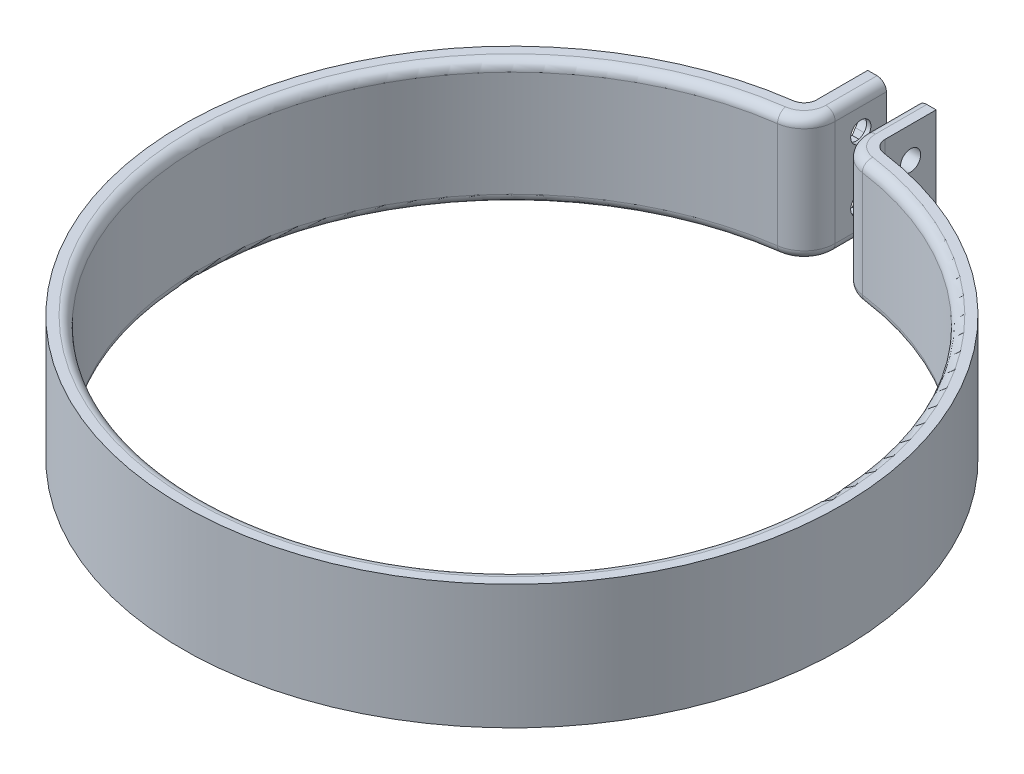
SolidWorks part; units mm, degrees
ref_plane "Front Plane" through (0, 0, 0) normal (0, 0, 1) x (1, 0, 0)
ref_plane "Top Plane" through (0, 0, 0) normal (0, 1, 0) x (1, 0, 0)
ref_plane "Right Plane" through (0, 0, 0) normal (1, 0, 0) x (0, 0, -1)
sketch "Sketch1" plane through (0, 0, 0) normal (0, 1, 0) x (1, 0, 0)
  line L0 (-74.3255, 0) -> (75.7723, 0) construction
  line L1 (0, 75.6818) -> (0, -79.2987) construction
  line L7 (2.5, 62.7139) -> (5.5, 62.7139)
  line L8 (2.5, 49.9375) -> (2.5, 62.7139)
  line L10 (-2.5, 49.9375) -> (-2.5, 62.7139)
  line L14 (-5.5, 52.7139) -> (-5.5, 62.7139)
  line L16 (5.5, 52.7139) -> (5.5, 62.7139)
  line L17 (2.5, 54.9432) -> (2.5, 67.7195) construction
  line L18 (-2.5, 62.7139) -> (-5.5, 62.7139)
  arc A1 (-2.5, 49.9375) -> (2.5, 49.9375) centre (0, 0) ccw
  arc A2 (-5.5, 52.7139) -> (5.5, 52.7139) centre (0, 0) ccw
  point P8 (-53, 0)
  point P9 (-50, 0)
  dimension "D1" = 3
  dimension "D2" = 100
  dimension "D5" = 10
  dimension "D6" = 5
  dimension "D7" = 3
  dimension "D8" = 5.5
extrude "Boss-Extrude1" add sketch "Sketch1" along normal blind 20
fillet "Fillet1" radius 5 2 edges at (-2.5, 10, -49.9375) (2.5, 10, -49.9375)
fillet "Fillet2" radius 2 2 edges at (-5.5, 10, -52.7139) (5.5, 10, -52.7139)
fillet "Fillet3" radius 1.5 10 edges at (-2.5, 0, -58.6) (-3.7311, 0, -51.2006) (-2.5, 20, -58.6) (-3.7311, 20, -51.2006) (0, 0, 50) (0, 20, 50) (2.5, 0, -58.6) (3.7311, 0, -51.2006) (2.5, 20, -58.6) (3.7311, 20, -51.2006)
sketch "Sketch4" plane through (-5.5, 0, 0) normal (-1, 0, 0) x (0, 0, 1)
  line L0 (-62.7139, 20) -> (-54.4862, 20) construction
  line L1 (-62.7139, 0) -> (-54.4862, 0) construction
  circle A0 centre (-58.6, 15) radius 2.9
  circle A1 centre (-58.6, 5) radius 2.9
  point P0 (-58.6, 20)
  point P1 (-58.6, 0)
  dimension "D1" = 5.8
  dimension "D2" = 5
  dimension "D3" = 5
extrude "Cut-Extrude3" cut sketch "Sketch4" against normal blind 2
sketch "Sketch5" plane through (-5.5, 0, 0) normal (-1, 0, 0) x (0, 0, 1)
  circle A0 centre (-58.6, 15) radius 1.625
  circle A1 centre (-58.6, 5) radius 1.625
  dimension "D1" = 3.25
extrude "Cut-Extrude4" cut sketch "Sketch5" against normal through all
sketch "Sketch6" plane through (-5.5, 0, 0) normal (-1, 0, 0) x (0, 0, 1)
  line L0 (-58.6, 17.825) -> (-58.6, 12.175) construction
  line L1 (-55.338, 15) -> (-56.969, 17.825)
  line L2 (-56.969, 17.825) -> (-60.2311, 17.825)
  line L3 (-60.2311, 17.825) -> (-61.8621, 15)
  line L4 (-61.8621, 15) -> (-60.2311, 12.175)
  line L5 (-60.2311, 12.175) -> (-56.969, 12.175)
  line L6 (-56.969, 12.175) -> (-55.338, 15)
  line L7 (-58.6, 7.825) -> (-58.6, 2.175) construction
  line L8 (-55.338, 5) -> (-56.969, 7.825)
  line L9 (-56.969, 7.825) -> (-60.2311, 7.825)
  line L10 (-60.2311, 7.825) -> (-61.8621, 5)
  line L11 (-61.8621, 5) -> (-60.2311, 2.175)
  line L12 (-60.2311, 2.175) -> (-56.969, 2.175)
  line L13 (-56.969, 2.175) -> (-55.338, 5)
  line L14 (-62.7139, 20) -> (-54.4862, 20) construction
  line L16 (-62.7139, 0) -> (-54.4862, 0) construction
  circle A0 centre (-58.6, 15) radius 2.825 construction
  circle A1 centre (-58.6, 5) radius 2.825 construction
  point P1 (-58.6, 17.825)
  point P9 (-58.6, 20)
  point P10 (-58.6, 12.175)
  point P14 (-58.6, 7.825)
  point P23 (-58.6, 2.175)
  dimension "D1" = 5.65
  dimension "D3" = 5
  dimension "D4" = 5
extrude "Cut-Extrude5" cut sketch "Sketch6" against normal blind 2.3
